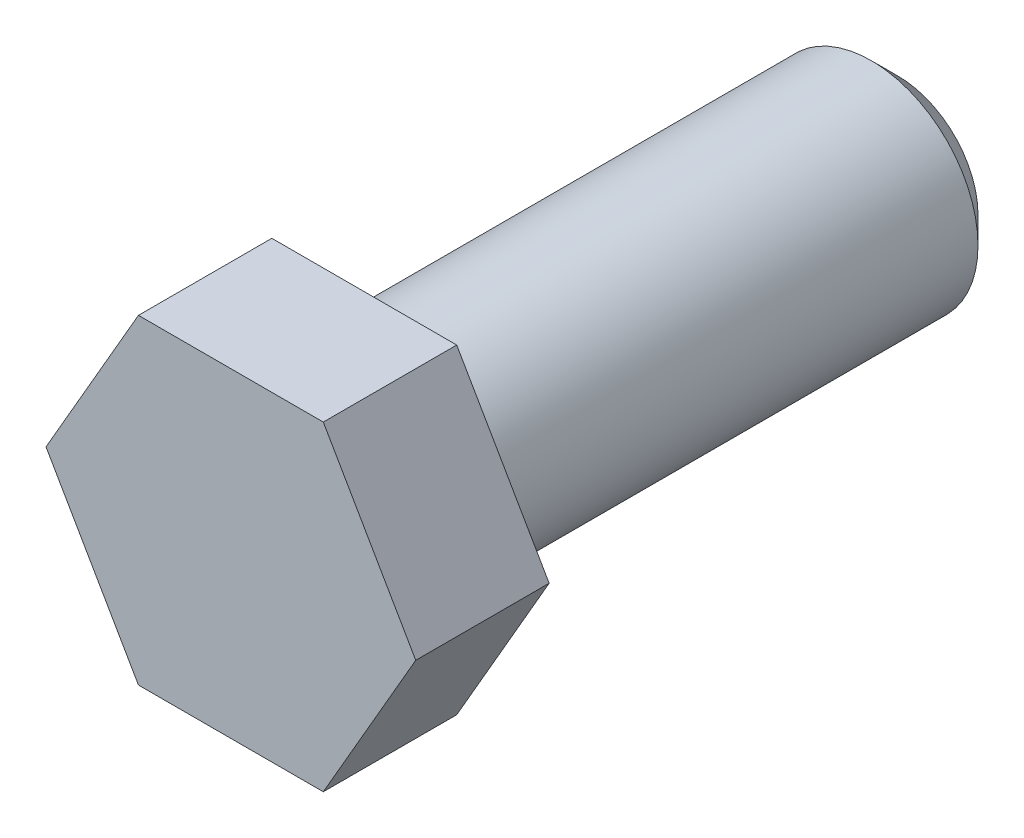
SolidWorks part; units mm, degrees
ref_plane "Plane1" through (0, 0, 0) normal (0, 0, 1) x (1, 0, 0)
ref_plane "MSC_PF1" through (0, 0, 0) normal (0, 1, 0) x (1, 0, 0)
ref_plane "Plane3" through (0, 0, 0) normal (1, 0, 0) x (0, 0, -1)
sketch "Sketch1" plane through (0, 0, 0) normal (0, 0, 1) x (1, 0, 0)
  line L0 (0, 0) -> (1, 0) construction
  line L1 (-5.1962, 9) -> (5.1962, 9)
  line L2 (-5.1962, -9) -> (5.1962, -9)
  line L3 (5.1962, 9) -> (10.3923, 0)
  line L4 (10.3923, 0) -> (5.1962, -9)
  line L5 (-5.1962, 9) -> (-10.3923, 0)
  line L6 (-10.3923, 0) -> (-5.1962, -9)
  circle A0 centre (0, 0) radius 9 construction
  dimension "P" = 1
  dimension "s" = 18
extrude "Base-Extrude" add sketch "Sketch1" along normal blind 7.5
sketch "Sketch3" plane through (0, 0, 0) normal (0, 0, -1) x (-1, 0, 0)
  circle A0 centre (0, 0) radius 6
  dimension "_d" = 12
extrude "Boss-Extrude1" add sketch "Sketch3" along normal blind 30
cosmetic thread "Условное изображение резьбы2" parameters "D2"=11
chamfer "Chamfer1" distance 1.5 angle 45 1 edges at (-6, 0, -30)
